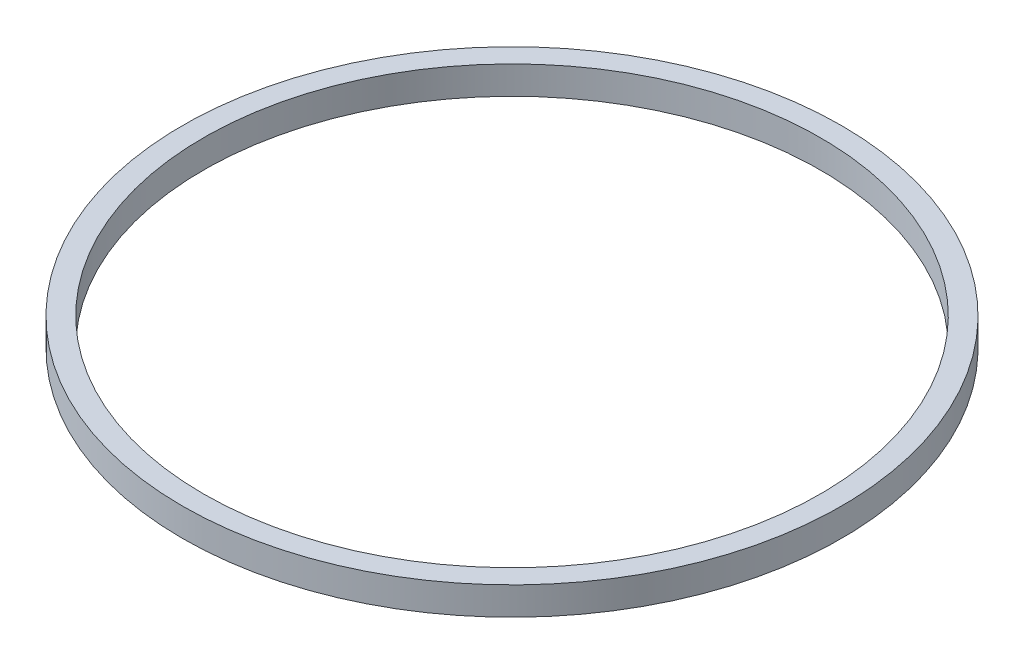
SolidWorks part; units mm, degrees
ref_plane "Front Plane" through (0, 0, 0) normal (0, 0, 1) x (1, 0, 0)
ref_plane "Top Plane" through (0, 0, 0) normal (0, 1, 0) x (1, 0, 0)
ref_plane "Right Plane" through (0, 0, 0) normal (1, 0, 0) x (0, 0, -1)
sketch "Sketch1" plane through (0, 0, 0) normal (0, 1, 0) x (1, 0, 0)
  circle A0 centre (0, 0) radius 11.75
  circle A1 centre (0, 0) radius 11
  dimension "D1" = 23.5
  dimension "D2" = 22
extrude "Boss-Extrude1" add sketch "Sketch1" along normal blind 1
